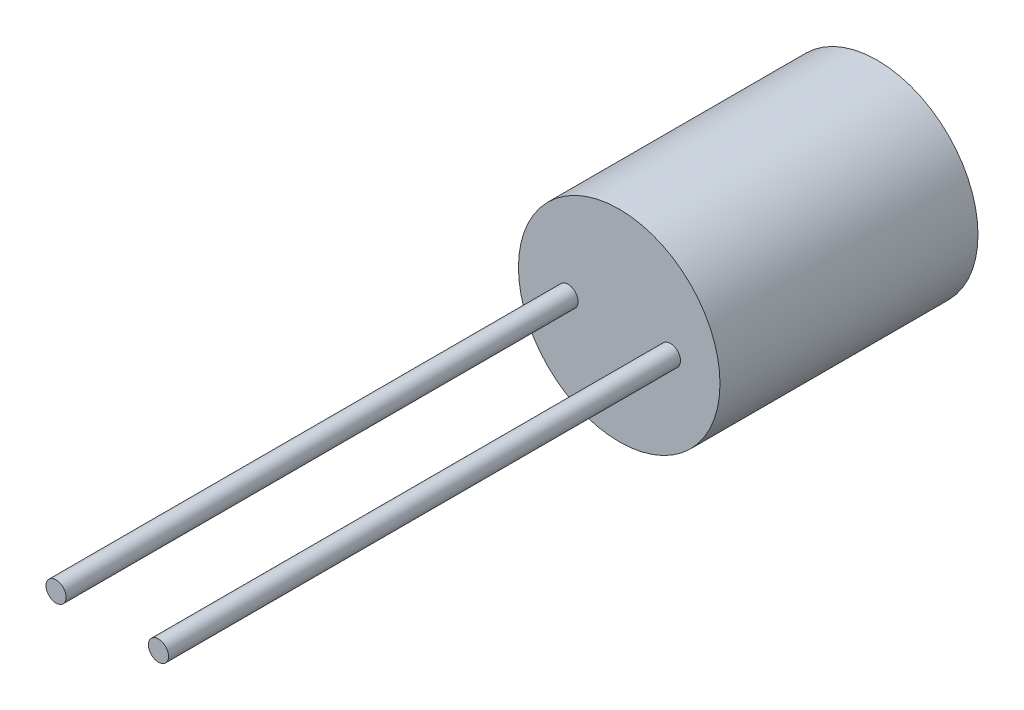
SolidWorks part; units mm, degrees
ref_plane "前视基准面" through (0, 0, 0) normal (0, 0, 1) x (1, 0, 0)
ref_plane "上视基准面" through (0, 0, 0) normal (0, 1, 0) x (1, 0, 0)
ref_plane "右视基准面" through (0, 0, 0) normal (1, 0, 0) x (0, 0, -1)
sketch "草图1" plane through (0, 0, 0) normal (0, 0, 1) x (1, 0, 0)
  circle A0 centre (0, 0) radius 2.5
  dimension "D1" = 5
extrude "拉伸1" add sketch "草图1" along normal blind 5.4
sketch "草图2" plane through (0, 0, 5.4) normal (0, 0, 1) x (1, 0, 0)
  circle A0 centre (0, 0) radius 2.5
  dimension "D1" = 5
extrude "拉伸2" add sketch "草图2" along normal blind 1
sketch "草图3" plane through (0, 0, 6.4) normal (0, 0, 1) x (1, 0, 0)
  line L0 (0, 2.011) -> (0, -2.1052) construction
  line L1 (-2.1813, 0) -> (2.3335, 0) construction
  circle A0 centre (-1.27, 0) radius 0.25
  circle A1 centre (1.27, 0) radius 0.25
  dimension "D1" = 0.5
  dimension "D2" = 2.54
extrude "拉伸3" add sketch "草图3" along normal blind 12.7
sketch "草图4" plane through (0, 0, 6.4) normal (0, 0, 1) x (1, 0, 0)
  point P0 (0, 0)
